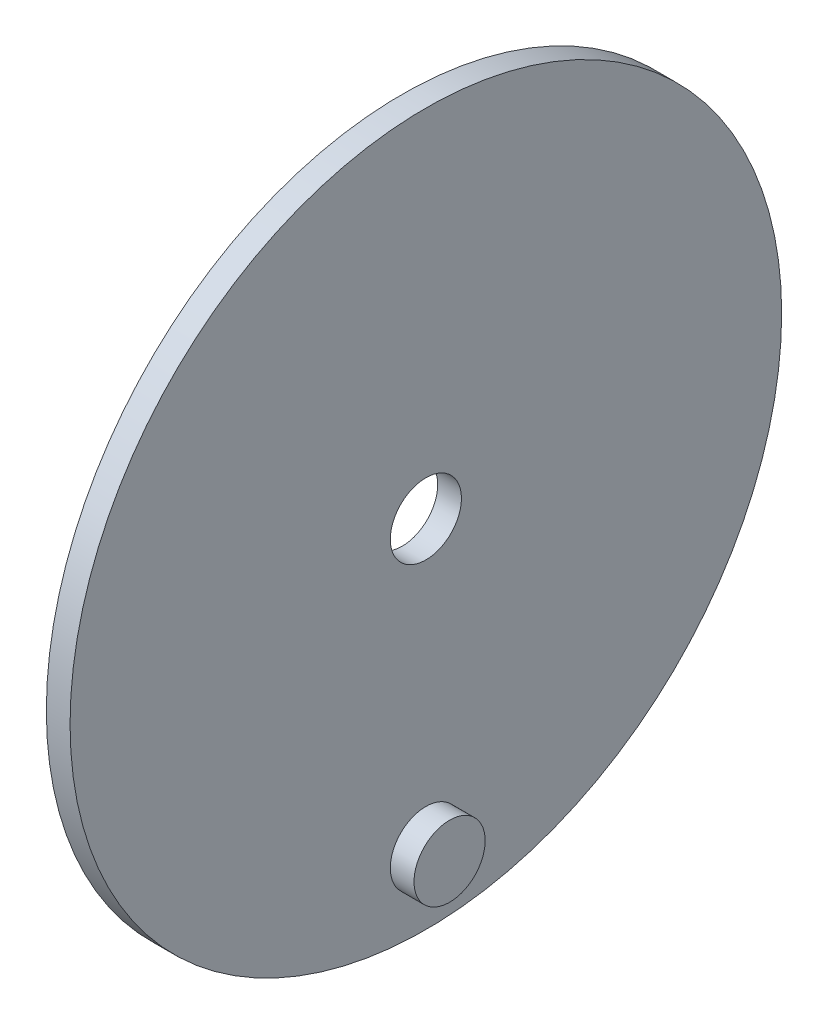
SolidWorks part; units mm, degrees
ref_plane "Front Plane" through (0, 0, 0) normal (0, 0, 1) x (1, 0, 0)
ref_plane "Top Plane" through (0, 0, 0) normal (0, 1, 0) x (1, 0, 0)
ref_plane "Right Plane" through (0, 0, 0) normal (1, 0, 0) x (0, 0, -1)
sketch "Sketch1" plane through (0, 0, 0) normal (1, 0, 0) x (0, 0, -1)
  circle A0 centre (0, 0) radius 150
  circle A1 centre (0, 0) radius 15
  dimension "D1" = 30
  dimension "D2" = 300
extrude "Boss-Extrude1" add sketch "Sketch1" along normal blind 10
sketch "Sketch2" plane through (10, 0, 0) normal (1, 0, 0) x (0, 0, -1)
  line L0 (0, 0) -> (0, -150) construction
  circle A0 centre (0, 0) radius 150 construction
  circle A1 centre (0, -120) radius 15
  dimension "D1" = 30
  dimension "D2" = 120
extrude "Boss-Extrude2" add sketch "Sketch2" along normal blind 10
sketch "Sketch3" plane through (20, 0, 0) normal (1, 0, 0) x (0, 0, -1)
  circle A1 centre (0, -120) radius 15
  circle A2 centre (0, -120) radius 15
  dimension "D1" = 0
